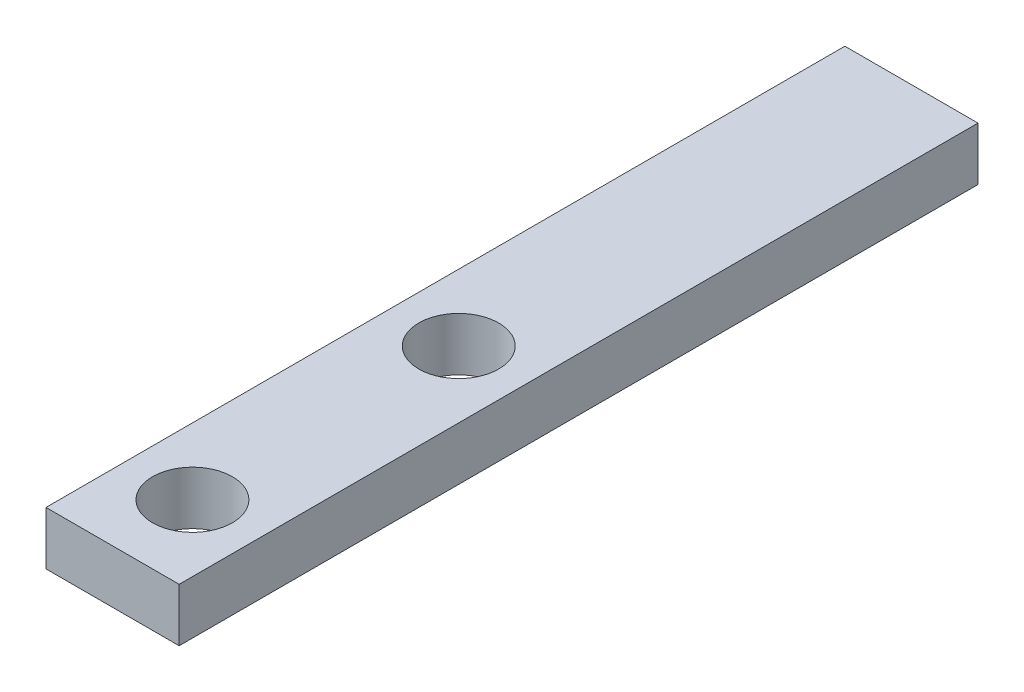
SolidWorks part; units mm, degrees
ref_plane "Front Plane" through (0, 0, 0) normal (0, 0, 1) x (1, 0, 0)
ref_plane "Top Plane" through (0, 0, 0) normal (0, 1, 0) x (1, 0, 0)
ref_plane "Right Plane" through (0, 0, 0) normal (1, 0, 0) x (0, 0, -1)
sketch "Sketch1" plane through (0, 0, 0) normal (0, 1, 0) x (1, 0, 0)
  line L1 (-2.5, 15) -> (2.5, 15)
  line L2 (-2.5, 15) -> (-2.5, -15)
  line L3 (-2.5, -15) -> (2.5, -15)
  line L4 (2.5, 15) -> (2.5, -15)
  line L5 (-2.5, 15) -> (2.5, -15) construction
  line L6 (-2.5, -15) -> (2.5, 15) construction
  circle A0 centre (0, -12) radius 1.5
  circle A1 centre (0, -2) radius 1.5
  point P0 (0, 0)
  point P10 (0, 0)
  point P11 (0, 0)
  point P12 (0, 3.7138)
  dimension "D2" = 3
  dimension "D3" = 3
  dimension "D1" = 5
  dimension "D4" = 10
  dimension "D5" = 3
  dimension "D6" = 30
extrude "Boss-Extrude1" add sketch "Sketch1" along normal blind 2
